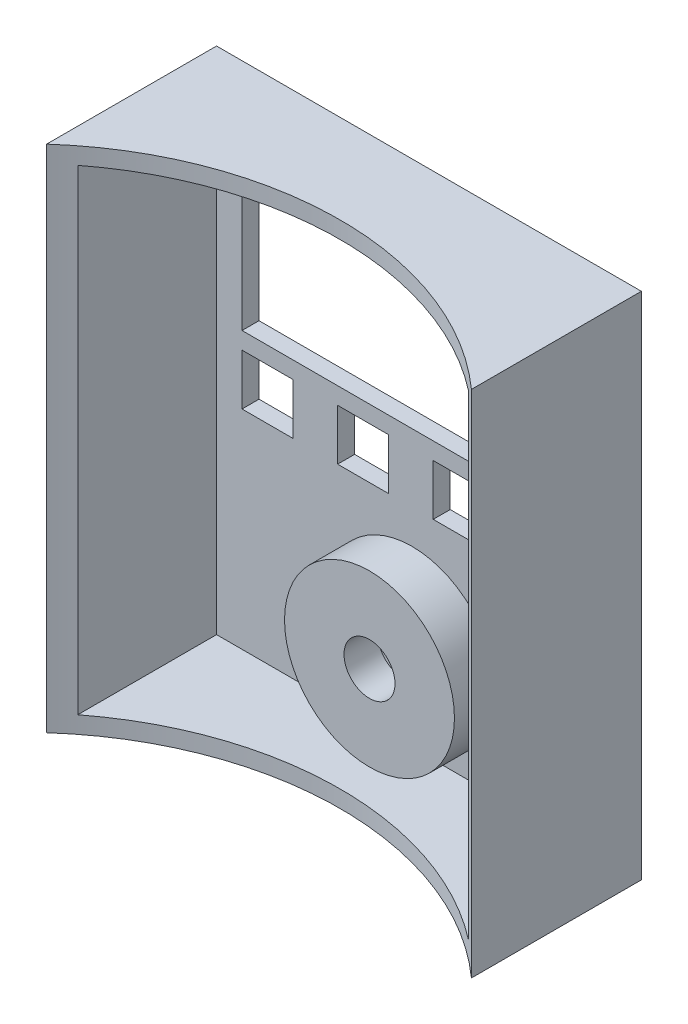
SolidWorks part; units mm, degrees
ref_plane "Front Plane" through (0, 0, 0) normal (0, 0, 1) x (1, 0, 0)
ref_plane "Top Plane" through (0, 0, 0) normal (0, 1, 0) x (1, 0, 0)
ref_plane "Right Plane" through (0, 0, 0) normal (1, 0, 0) x (0, 0, -1)
sketch "Sketch1" plane through (0, 0, 0) normal (0, 0, 1) x (1, 0, 0)
  line L1 (0, 0) -> (100, 0)
  line L2 (0, 0) -> (0, -120)
  line L3 (0, -120) -> (100, -120)
  line L4 (100, 0) -> (100, -120)
  dimension "D1" = 100
  dimension "D2" = 120
extrude "Boss-Extrude1" add sketch "Sketch1" along normal blind 40
sketch "Sketch2" plane through (0, 0, 0) normal (0, 1, 0) x (1, 0, 0)
  line L0 (100, 0) -> (0, 0) construction
  line L1 (0, -40) -> (100, -40)
  arc A0 (0, -40) -> (100, -40) centre (50, -95.9017) cw
  point P8 (50, -20.9017)
  dimension "D1" = 75
  dimension "D2" = 20.9017
extrude "Cut-Extrude2" cut sketch "Sketch2" against normal blind 120
shell "Shell1" thickness 4
sketch "Sketch3" plane through (0, 0, 0) normal (0, 0, -1) x (-1, 0, 0)
  line L0 (-100, 0) -> (0, 0) construction
  line L1 (-90, -15) -> (-10, -15)
  line L2 (-90, -15) -> (-90, -51)
  line L3 (-90, -51) -> (-10, -51)
  line L4 (-10, -15) -> (-10, -51)
  line L5 (0, 0) -> (0, -120) construction
  point P6 (-50, -15)
  point P7 (-90, -33)
  dimension "D1" = 15
  dimension "D2" = 36
  dimension "D3" = 80
  dimension "D4" = 10
extrude "Cut-Extrude3" cut sketch "Sketch3" against normal through all and the other way through all
sketch "Sketch4" plane through (0, 0, 4) normal (0, 0, 1) x (1, 0, 0)
  circle A0 centre (50, -95) radius 20
extrude "Boss-Extrude2" add sketch "Sketch4" along normal blind 10
sketch "Sketch6" plane through (0, 0, 4) normal (0, 0, 1) x (1, 0, 0)
  line L1 (27.5, -6) -> (72.5, -6)
  line L2 (27.5, -6) -> (27.5, -12)
  line L3 (27.5, -12) -> (72.5, -12)
  line L4 (72.5, -6) -> (72.5, -12)
extrude "Boss-Extrude4" add sketch "Sketch6" along normal blind 8
sketch "Sketch7" plane through (0, 0, 12) normal (0, 0, 1) x (1, 0, 0)
  circle A0 centre (50, -9) radius 2.5
extrude "Cut-Extrude6" cut sketch "Sketch7" against normal through all
pattern_linear "LPattern2" count 2 spacing 15 along (-1, 0, 0) count 2 spacing 15 along (1, 0, 0) of "Cut-Extrude6"
sketch "Sketch9" plane through (0, 0, 4) normal (0, 0, 1) x (1, 0, 0)
  line L1 (10, -55) -> (22, -55)
  line L2 (10, -55) -> (10, -67)
  line L3 (10, -67) -> (22, -67)
  line L4 (22, -55) -> (22, -67)
extrude "Cut-Extrude7" cut sketch "Sketch9" against normal blind 10
pattern_linear "LPattern3" count 4 spacing 22.5 along (1, 0, 0) of "Cut-Extrude7"
sketch "Sketch10" plane through (0, 0, 14) normal (0, 0, 1) x (1, 0, 0)
  circle A0 centre (50, -95) radius 6
extrude "Cut-Extrude8" cut sketch "Sketch10" against normal blind 8
sketch "Sketch13" plane through (0, 0, 6) normal (0, 0, 1) x (1, 0, 0)
  circle A0 centre (50, -95) radius 0.5
extrude "Cut-Extrude9" cut sketch "Sketch13" against normal blind 10
sketch "Sketch14" plane through (0, 0, 6) normal (0, 0, 1) x (1, 0, 0)
  line L0 (44, -95) -> (56, -95) construction
  circle A0 centre (50, -95) radius 6 construction
  circle A1 centre (50, -95) radius 6 construction
pattern_linear "LPattern4" count 3 spacing 2 along (1, 0, 0) count 3 spacing 2 along (-1, 0, 0) of "Cut-Extrude9"
pattern_circular "CirPattern2" count 6 every 60 about axis through (50, -95, 0) along (0, 0, 1) of "LPattern4"
